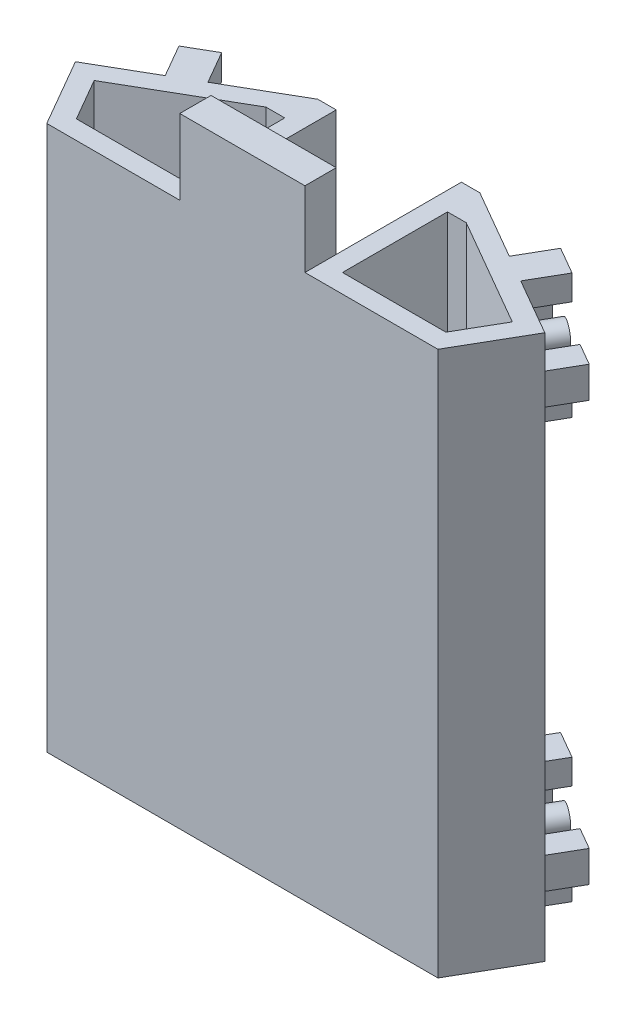
SolidWorks part; units mm, degrees
ref_plane "Plan de face" through (0, 0, 0) normal (0, 0, 1) x (1, 0, 0)
ref_plane "Plan de dessus" through (0, 0, 0) normal (0, 1, 0) x (1, 0, 0)
ref_plane "Plan de droite" through (0, 0, 0) normal (1, 0, 0) x (0, 0, -1)
sketch "Esquisse1" plane through (0, 0, 0) normal (0, 1, 0) x (1, 0, 0)
  line L0 (-31.25, 0) -> (31.25, 0)
  line L1 (31.25, 0) -> (37.5, 10.8253)
  line L2 (37.5, 10.8253) -> (12.9487, 25)
  line L3 (12.9487, 25) -> (10, 25)
  line L4 (10, 25) -> (10, 5)
  line L5 (10, 5) -> (-10, 5)
  line L6 (-10, 5) -> (-10, 25)
  line L7 (-10, 25) -> (-12.9487, 25)
  line L8 (-12.9487, 25) -> (-37.5, 10.8253)
  line L9 (-37.5, 10.8253) -> (-31.25, 0)
  line L10 (0, 5) -> (0, 0) construction
  dimension "D1" = 120
  dimension "D2" = 5
  dimension "D3" = 20
  dimension "D4" = 62.5
  dimension "D5" = 12.5
extrude "Boss.-Extru.1" add sketch "Esquisse1" along normal up to surface (87 mm away)
sketch "Esquisse2" plane through (0, 87, 0) normal (0, 1, 0) x (1, 0, 0)
  line L0 (-36, 8.2272) -> (-16, 19.7742)
  line L1 (-16, 19.7742) -> (-13, 19.7742)
  line L3 (-37.5, 10.8253) -> (-12.9487, 25) construction
  line L4 (-31.25, 0) -> (-37.5, 10.8253) construction
  line L6 (-13, 19.7742) -> (-13, 0)
  line L7 (31.25, 0) -> (-31.25, 0) construction
  line L8 (-13, 0) -> (-31.25, 0)
  line L9 (-31.25, 0) -> (-36, 8.2272)
  line L10 (-10, 25) -> (-10, 5) construction
  dimension "D1" = 3
  dimension "D2" = 3
  dimension "D3" = 3
extrude "Enlèv. mat.-Extru.1" cut sketch "Esquisse2" against normal up to next
mirror "Symétrie1" about plane through (0, 0, 0) normal (1, 0, 0) of "Enlèv. mat.-Extru.1"
sketch "Esquisse3" plane through (-14.0625, 0, -24.357) normal (0.5, 0, 0.866) x (0.866, 0, -0.5)
  line L0 (-27.0633, 87) -> (-27.0633, 0) construction
  line L4 (-3.9693, 87) -> (-27.0633, 87) construction
  line L5 (-14.0633, 83) -> (-14.0633, 71) construction
  line L6 (-11.5633, 87) -> (-16.5633, 87)
  line L7 (-11.5633, 87) -> (-11.5633, 83)
  line L8 (-11.5633, 83) -> (-16.5633, 83)
  line L9 (-16.5633, 87) -> (-16.5633, 83)
  line L10 (-20.0633, 79.5) -> (-24.0633, 79.5)
  line L11 (-20.0633, 79.5) -> (-20.0633, 74.5)
  line L12 (-20.0633, 74.5) -> (-24.0633, 74.5)
  line L13 (-24.0633, 79.5) -> (-24.0633, 74.5)
  line L14 (-4.0633, 79.5) -> (-8.0633, 79.5)
  line L15 (-4.0633, 79.5) -> (-4.0633, 74.5)
  line L16 (-4.0633, 74.5) -> (-8.0633, 74.5)
  line L17 (-8.0633, 79.5) -> (-8.0633, 74.5)
  line L18 (-11.5633, 71) -> (-16.5633, 71)
  line L19 (-11.5633, 71) -> (-11.5633, 67)
  line L20 (-11.5633, 67) -> (-16.5633, 67)
  line L21 (-16.5633, 71) -> (-16.5633, 67)
  line L23 (-8.0633, 77) -> (-20.0633, 77) construction
  circle A1 centre (-14.0633, 77) radius 1.9
  point P7 (0, 0)
  point P27 (-9.2073, 78.616)
  dimension "D1" = 5
  dimension "D2" = 4
  dimension "D3" = 10
  dimension "D4" = 3.8
  dimension "D5" = 20
  dimension "D6" = 13
sketch "Esquisse4" plane through (0, 0, 0) normal (0, 1, 0) x (1, 0, 0)
  line L0 (-37.5, 10.8253) -> (-31.25, 0)
  line L1 (-31.25, 0) -> (31.25, 0)
  line L2 (31.25, 0) -> (37.5, 10.8253)
  line L3 (12.9487, 25) -> (37.5, 10.8253) construction
  line L4 (37.5, 10.8253) -> (36, 8.2272) construction
  line L5 (-36, 8.2272) -> (-37.5, 10.8253) construction
  line L6 (-37.5, 10.8253) -> (-34.9019, 12.3253)
  line L7 (-37.5, 10.8253) -> (-12.9487, 25) construction
  line L8 (-34.9019, 12.3253) -> (-29.5179, 3)
  line L9 (-29.5179, 3) -> (29.5179, 3)
  line L10 (29.5179, 3) -> (34.9019, 12.3253)
  line L11 (34.9019, 12.3253) -> (37.5, 10.8253)
  line L12 (0, 0) -> (0, 3) construction
  dimension "D1" = 3
extrude "Boss.-Extru.2" add sketch "Esquisse4" along normal up to surface (87 mm away) up to face at (0, 87, -14.2001)
extrude "Boss.-Extru.3" add sketch "Esquisse3" against normal blind 6
ref_plane "Plan1" through (0, 43.5, 0) normal (0, 1, 0) x (1, 0, 0)
mirror "Symétrie2" about plane through (0, 43.5, 0) normal (0, 1, 0) of "Boss.-Extru.3"
mirror "Symétrie3" about plane through (0, 0, 0) normal (1, 0, 0) of "Symétrie2", "Boss.-Extru.3"
sketch "Esquisse5" plane through (0, 87, 0) normal (0, 1, 0) x (1, 0, 0)
  line L0 (31.25, 0) -> (-31.25, 0) construction
  line L1 (-10, 5) -> (10, 5)
  line L2 (-10, 5) -> (-10, 0)
  line L3 (-10, 0) -> (10, 0)
  line L4 (10, 5) -> (10, 0)
  line L5 (10, 5) -> (10, 25) construction
extrude "Boss.-Extru.4" add sketch "Esquisse5" along normal blind 12
